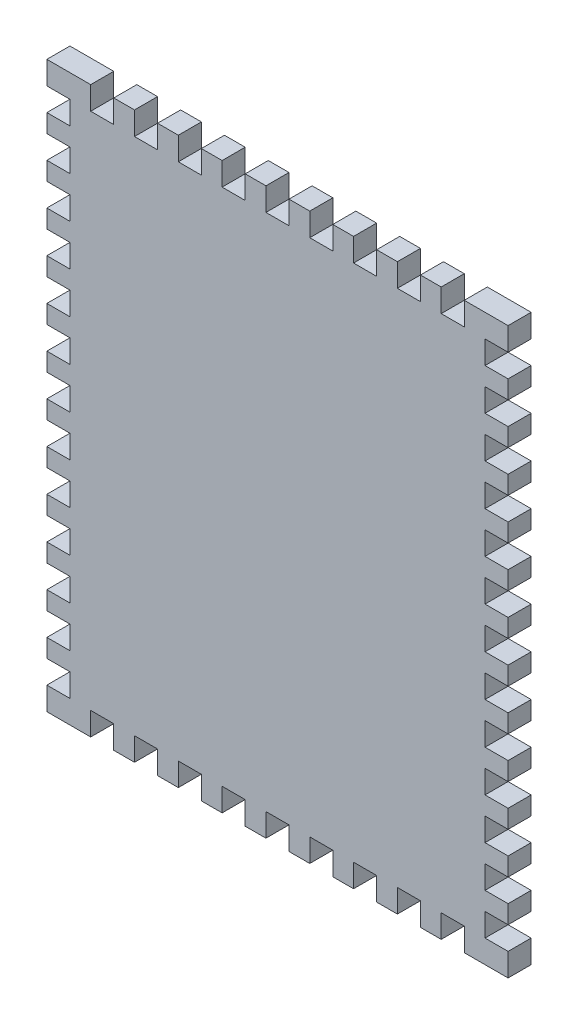
SolidWorks part; units mm, degrees
ref_plane "Plano frontal" through (0, 0, 0) normal (0, 0, 1) x (1, 0, 0)
ref_plane "Plano superior" through (0, 0, 0) normal (0, 1, 0) x (1, 0, 0)
ref_plane "Plano direito" through (0, 0, 0) normal (1, 0, 0) x (0, 0, -1)
sketch "Esboço1" plane through (0, 0, 0) normal (0, 0, 1) x (1, 0, 0)
  line L0 (0, 0) -> (0, 73.5) construction
  line L1 (60, -73.5) -> (-60, -73.5)
  line L2 (60, -73.5) -> (60, 73.5)
  line L3 (60, 73.5) -> (-60, 73.5)
  line L4 (-60, -73.5) -> (-60, 73.5)
  line L5 (60, -73.5) -> (-60, 73.5) construction
  line L6 (60, 73.5) -> (-60, -73.5) construction
  point P0 (0, 0)
  dimension "D1" = 120
  dimension "D2" = 147
extrude "Ressalto-extrusão1" add sketch "Esboço1" along normal blind 6
sketch "Esboço2" plane through (0, 0, 6) normal (0, 0, 1) x (1, 0, 0)
  line L0 (0, 0) -> (0, 73.5) construction
  line L1 (60, 73.5) -> (-60, 73.5) construction
  line L2 (-3, 67.5) -> (3, 67.5)
  line L3 (-3, 67.5) -> (-3, 73.5)
  line L4 (3, 67.5) -> (3, 73.5)
  line L5 (0, 0) -> (0, -73.5) construction
  line L6 (-60, -73.5) -> (60, -73.5) construction
  point P8 (0, 67.5)
  point P16 (0, -73.5)
  dimension "D1" = 6
  dimension "D2" = 6
extrude "Corte-extrusão1" cut sketch "Esboço2" against normal through all and the other way through all
sketch "Esboço3" plane through (0, 0, 6) normal (0, 0, 1) x (1, 0, 0)
  line L0 (0, 0) -> (-60, 0) construction
  line L1 (-60, 73.5) -> (-60, -73.5) construction
  line L2 (-60, -3) -> (-60, 3)
  line L3 (-60, -3) -> (-54, -3)
  line L4 (-54, -3) -> (-54, 3)
  line L5 (-54, 3) -> (-60, 3)
  line L6 (60, -3) -> (60, 3)
  line L7 (60, -73.5) -> (60, 73.5) construction
  line L8 (60, -3) -> (54, -3)
  line L9 (54, -3) -> (54, 3)
  line L10 (54, 3) -> (60, 3)
  point P8 (-60, 0)
  point P15 (60, 0)
  dimension "D1" = 6
  dimension "D2" = 6
  dimension "D3" = 6
  dimension "D4" = 6
extrude "Corte-extrusão2" cut sketch "Esboço3" against normal through all
pattern_linear "Padrão linear1" count 7 spacing 10.75 along (0, 1, 0) count 7 spacing 10.75 along (0, -1, 0) of "Corte-extrusão2"
pattern_linear "Padrão linear2" count 5 spacing 11.4 along (-1, 0, 0) of "Corte-extrusão1"
pattern_linear "Padrão linear3" count 5 spacing 11.4 along (1, 0, 0) of "Corte-extrusão1"
sketch "Esboço4" plane through (0, 0, 6) normal (0, 0, 1) x (1, 0, 0)
  line L0 (0, 0) -> (0, -73.5) construction
  line L1 (-60, -73.5) -> (60, -73.5) construction
  line L2 (-3, -73.5) -> (3, -73.5)
  line L3 (3, -73.5) -> (3, -67.5)
  line L4 (3, -67.5) -> (-3, -67.5)
  line L5 (-3, -67.5) -> (-3, -73.5)
  point P8 (0, -73.5)
  dimension "D1" = 6
  dimension "D2" = 6
extrude "Corte-extrusão3" cut sketch "Esboço4" against normal through all
pattern_linear "Padrão linear4" count 5 spacing 11.4 along (-1, 0, 0) of "Corte-extrusão3"
pattern_linear "Padrão linear5" count 5 spacing 11.4 along (1, 0, 0) of "Corte-extrusão3"
